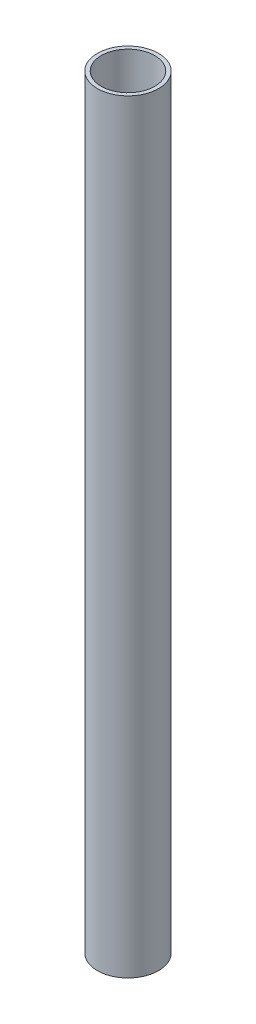
SolidWorks part; units mm, degrees
ref_plane "前视基准面" through (0, 0, 0) normal (0, 0, 1) x (1, 0, 0)
ref_plane "上视基准面" through (0, 0, 0) normal (0, 1, 0) x (1, 0, 0)
ref_plane "右视基准面" through (0, 0, 0) normal (1, 0, 0) x (0, 0, -1)
sketch "草图1" plane through (0, 0, 0) normal (0, 1, 0) x (1, 0, 0)
  circle A0 centre (0, 0) radius 8
  circle A1 centre (0, 0) radius 7
  dimension "D1" = 16
  dimension "D2" = 14
extrude "凸台-拉伸1" add sketch "草图1" along normal blind 200
